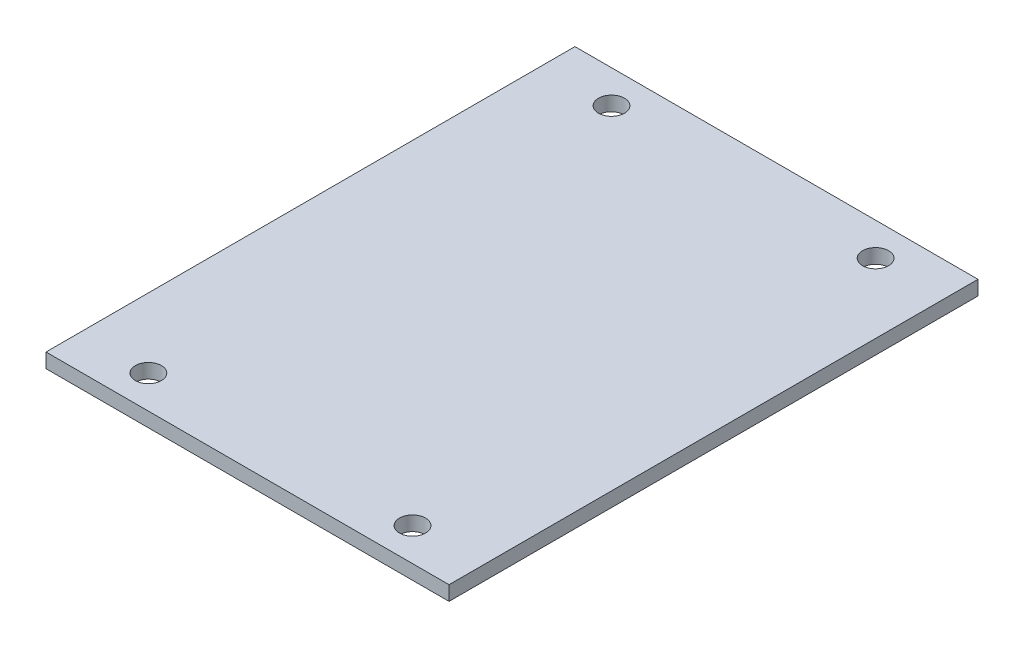
SolidWorks part; units mm, degrees
ref_plane "Front Plane" through (0, 0, 0) normal (0, 0, 1) x (1, 0, 0)
ref_plane "Top Plane" through (0, 0, 0) normal (0, 1, 0) x (1, 0, 0)
ref_plane "Right Plane" through (0, 0, 0) normal (1, 0, 0) x (0, 0, -1)
sketch "Sketch2" plane through (0, 0, 0) normal (0, 1, 0) x (1, 0, 0)
  line L1 (27.85, 36.55) -> (-27.85, 36.55)
  line L2 (27.85, 36.55) -> (27.85, -36.55)
  line L3 (27.85, -36.55) -> (-27.85, -36.55)
  line L4 (-27.85, 36.55) -> (-27.85, -36.55)
  line L5 (27.85, 36.55) -> (-27.85, -36.55) construction
  line L6 (27.85, -36.55) -> (-27.85, 36.55) construction
  point P0 (0, 0)
  dimension "D1" = 73.1
  dimension "D2" = 55.7
extrude "Boss-Extrude1" add sketch "Sketch2" along normal blind 2
sketch "Sketch3" plane through (0, 2, 0) normal (0, 1, 0) x (1, 0, 0)
  line L1 (18.25, 32) -> (-18.25, 32) construction
  line L2 (18.25, 32) -> (18.25, -32) construction
  line L3 (18.25, -32) -> (-18.25, -32) construction
  line L4 (-18.25, 32) -> (-18.25, -32) construction
  line L5 (18.25, 32) -> (-18.25, -32) construction
  line L6 (18.25, -32) -> (-18.25, 32) construction
  circle A0 centre (-18.25, 32) radius 1.8
  circle A1 centre (18.25, 32) radius 1.8
  circle A2 centre (-18.25, -32) radius 1.8
  circle A3 centre (18.25, -32) radius 1.8
  point P0 (0, 0)
  dimension "D3" = 3.6
  dimension "D1" = 64
  dimension "D2" = 36.5
extrude "Cut-Extrude1" cut sketch "Sketch3" against normal through all
